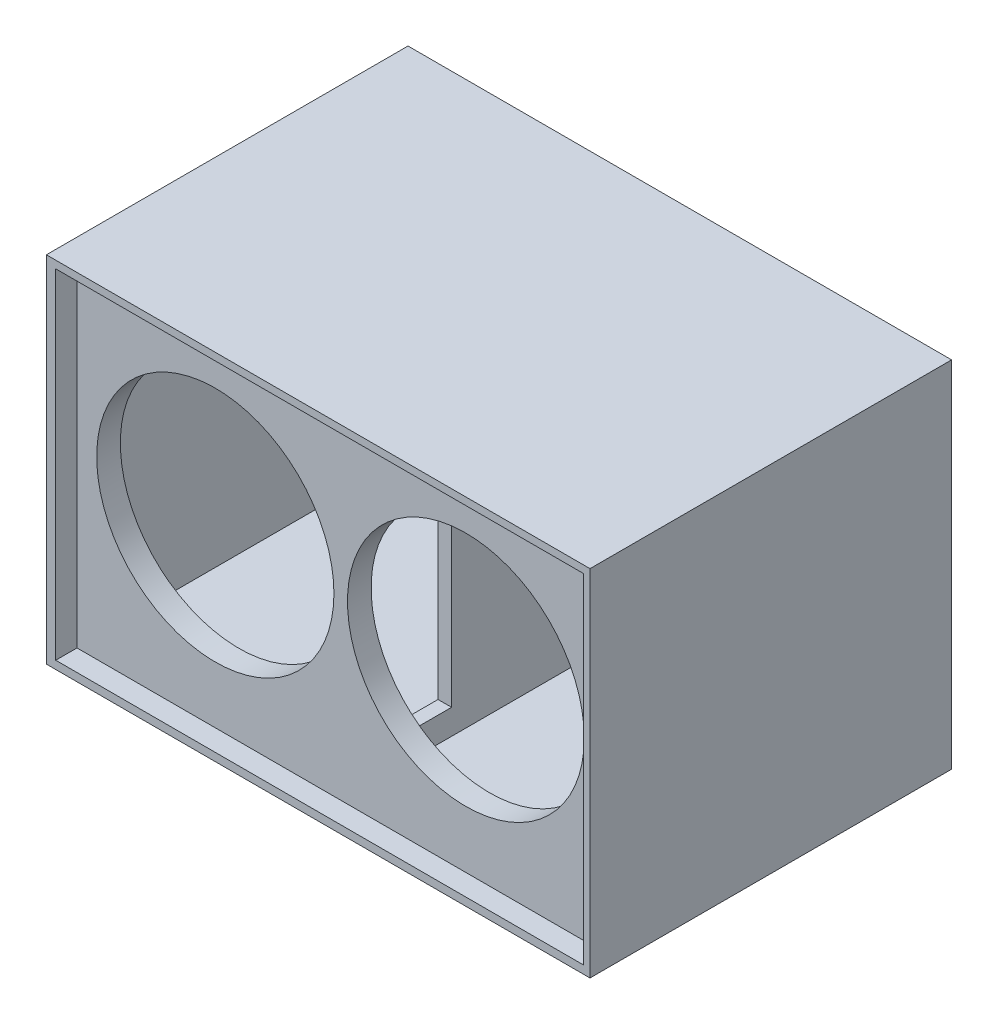
SolidWorks part; units mm, degrees
ref_plane "Front Plane" through (0, 0, 0) normal (0, 0, 1) x (1, 0, 0)
ref_plane "Top Plane" through (0, 0, 0) normal (0, 1, 0) x (1, 0, 0)
ref_plane "Right Plane" through (0, 0, 0) normal (1, 0, 0) x (0, 0, -1)
sketch "Sketch1" plane through (0, 0, 0) normal (0, 0, 1) x (1, 0, 0)
  line L1 (-110.8587, 72.313) -> (119.1413, 72.313)
  line L2 (-110.8587, 72.313) -> (-110.8587, -77.687)
  line L3 (-110.8587, -77.687) -> (119.1413, -77.687)
  line L4 (119.1413, 72.313) -> (119.1413, -77.687)
  dimension "D1" = 230
  dimension "D2" = 150
extrude "Boss-Extrude1" add sketch "Sketch1" along normal blind 150
sketch "Sketch2" plane through (0, 0, 150) normal (0, 0, 1) x (1, 0, 0)
  circle A0 centre (-48.3853, 0) radius 50.1883
  circle A1 centre (57.6272, 0) radius 50.088
extrude "Cut-Extrude1" cut sketch "Sketch2" against normal blind 27
sketch "Sketch3" plane through (0, 0, 0) normal (0, 0, -1) x (-1, 0, 0)
  line L1 (-113.7515, 66.2691) -> (105.469, 66.2691)
  line L2 (-113.7515, 66.2691) -> (-113.7515, -72.6025)
  line L3 (-113.7515, -72.6025) -> (105.469, -72.6025)
  line L4 (105.469, 66.2691) -> (105.469, -72.6025)
extrude "Cut-Extrude2" cut sketch "Sketch3" against normal blind 134
sketch "Sketch4" plane through (0, 0, 150) normal (0, 0, 1) x (1, 0, 0)
  line L1 (-110.8587, 72.313) -> (119.1413, 72.313)
  line L2 (-110.8587, 72.313) -> (-110.8587, -77.687)
  line L3 (-110.8587, -77.687) -> (119.1413, -77.687)
  line L4 (119.1413, 72.313) -> (119.1413, -77.687)
extrude "Boss-Extrude2" add sketch "Sketch4" along normal blind 3
sketch "Sketch5" plane through (0, 0, 153) normal (0, 0, 1) x (1, 0, 0)
  line L1 (-106.908, 69.1473) -> (116.3898, 69.1473)
  line L2 (-106.908, 69.1473) -> (-106.908, -74.2814)
  line L3 (-106.908, -74.2814) -> (116.3898, -74.2814)
  line L4 (116.3898, 69.1473) -> (116.3898, -74.2814)
extrude "Cut-Extrude3" cut sketch "Sketch5" against normal blind 9
sketch "Sketch7" plane through (0, 0, 134) normal (0, 0, -1) x (-1, 0, 0)
  line L0 (105.469, 66.2691) -> (-113.7515, 66.2691) construction
  line L1 (-10.1456, 66.2691) -> (0, 66.2691)
  line L3 (-10.1456, -72.6025) -> (0, -72.6025)
  line L4 (-7.5393, 66.2691) -> (-1.803, 66.2691)
  line L5 (-113.7515, -72.6025) -> (105.469, -72.6025) construction
  line L6 (-7.5393, 66.2691) -> (-7.5393, -71.4593)
  line L7 (-7.5393, 66.2691) -> (-1.803, 66.2691)
  line L8 (-7.5393, -71.4593) -> (-1.803, -71.4593)
  line L9 (-7.5393, -72.6025) -> (-1.803, -72.6025)
  line L10 (-1.803, 66.2691) -> (-1.803, -71.4593)
extrude "Boss-Extrude5" add sketch "Sketch7" along normal blind 110 contours L10 L1 L6 L8
sketch "Sketch8" plane through (0, 0, 0) normal (0, 0, -1) x (-1, 0, 0)
  circle A0 centre (-116.2157, 69.3437) radius 1.5
  circle A1 centre (108.1737, -74.4772) radius 1.5
extrude "Cut-Extrude4" cut sketch "Sketch8" against normal blind 10
sketch "Sketch9" plane through (7.5393, 0, 0) normal (1, 0, 0) x (0, 0, -1)
  line L0 (-134, 0) -> (-134, -71.4593) construction
  line L1 (-134, 55.0579) -> (-99.955, 55.0579)
  line L2 (-134, 55.0579) -> (-134, -60.8218)
  line L3 (-134, -60.8218) -> (-99.955, -60.8218)
  line L4 (-99.955, 55.0579) -> (-99.955, -60.8218)
  point P4 (-100.5697, 55.0579)
  point P5 (-99.955, -60.8481)
  point P6 (0, 0)
  point P7 (0, 0)
  point P8 (0, 0)
  point P9 (-134, -60.8218)
extrude "Cut-Extrude5" cut sketch "Sketch9" against normal blind 10
